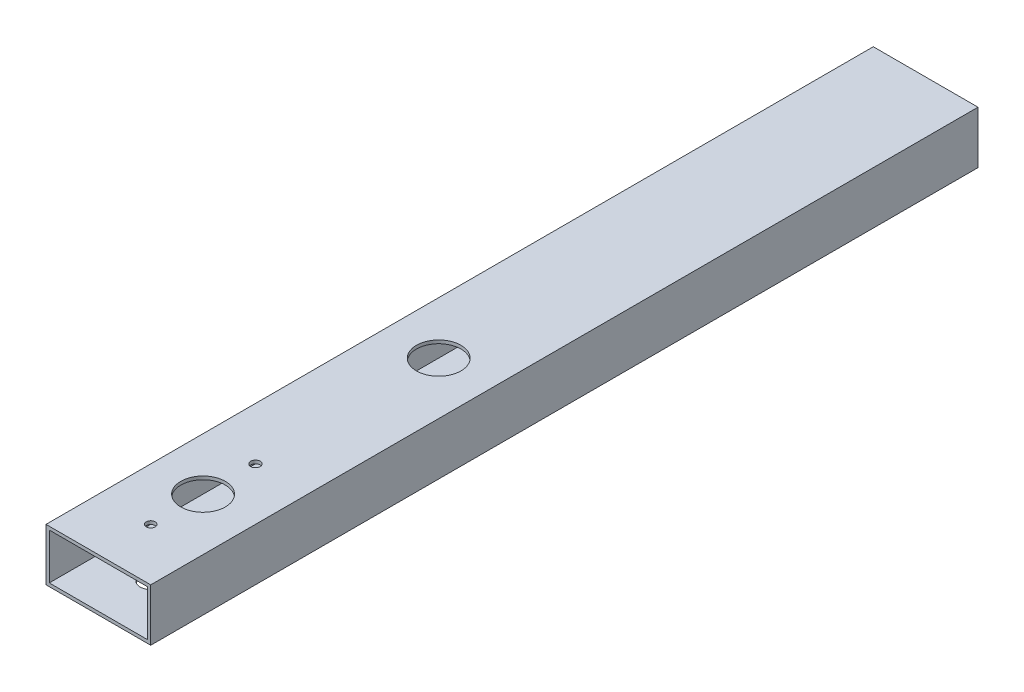
SolidWorks part; units mm, degrees
ref_plane "Front Plane" through (0, 0, 0) normal (0, 0, 1) x (1, 0, 0)
ref_plane "Top Plane" through (0, 0, 0) normal (0, 1, 0) x (1, 0, 0)
ref_plane "Right Plane" through (0, 0, 0) normal (1, 0, 0) x (0, 0, -1)
sketch "Sketch1" plane through (0, 0, 0) normal (0, 0, 1) x (1, 0, 0)
  line L0 (1.5875, 1.5875) -> (1.5875, 23.8125)
  line L1 (0, 0) -> (50.8, 0)
  line L2 (0, 0) -> (0, 25.4)
  line L3 (0, 25.4) -> (50.8, 25.4)
  line L4 (50.8, 0) -> (50.8, 25.4)
  line L5 (1.5875, 23.8125) -> (49.2125, 23.8125)
  line L6 (49.2125, 1.5875) -> (49.2125, 23.8125)
  line L7 (1.5875, 1.5875) -> (49.2125, 1.5875)
  dimension "D1" = 25.4
  dimension "D2" = 50.8
  dimension "D3" = 1.5875
extrude "Boss-Extrude1" add sketch "Sketch1" along normal blind 401.32
sketch "Sketch2" plane through (0, 25.4, 0) normal (0, 1, 0) x (1, 0, 0)
  line L1 (50.8, -401.32) -> (0, -401.32) construction
  line L2 (50.8, -401.32) -> (50.8, 0) construction
  circle A1 centre (25.4, -236.22) radius 10.795
  dimension "D1" = 21.59
  dimension "D2" = 165.1
  dimension "D6" = 25.4
extrude "Cut-Extrude1" cut sketch "Sketch2" against normal blind 2.54
sketch "Sketch3" plane through (0, 25.4, 0) normal (0, 1, 0) x (1, 0, 0)
  line L0 (50.8, -401.32) -> (50.8, 0) construction
  line L1 (50.8, -401.32) -> (0, -401.32) construction
  circle A0 centre (25.4, -350.52) radius 10.795
  dimension "D1" = 21.59
  dimension "D2" = 25.4
  dimension "D3" = 50.8
extrude "Cut-Extrude2" cut sketch "Sketch3" against normal blind 4.92
sketch "Sketch5" plane through (0, 1.5875, 0) normal (0, 1, 0) x (1, 0, 0)
  line L0 (50.8, -401.32) -> (50.8, 0) construction
  line L1 (1.5875, -401.32) -> (49.2125, -401.32) construction
  circle A0 centre (25.4, -236.22) radius 14.351
  dimension "D1" = 28.702
  dimension "D2" = 25.4
  dimension "D3" = 165.1
extrude "Cut-Extrude3" cut sketch "Sketch5" against normal blind 12.7
sketch "Sketch6" plane through (0, 1.5875, 0) normal (0, 1, 0) x (1, 0, 0)
  circle A0 centre (25.4, -350.52) radius 14.351
  dimension "D1" = 28.702
extrude "Cut-Extrude4" cut sketch "Sketch6" against normal blind 12.7
sketch "Sketch7" plane through (0, 25.4, 0) normal (0, 1, 0) x (1, 0, 0)
  line L0 (50.8, -401.32) -> (0, -401.32) construction
  line L1 (50.8, -401.32) -> (50.8, 0) construction
  circle A0 centre (25.4, -375.92) radius 2.159
  point P4 (0, 0)
  dimension "D1" = 4.318
  dimension "D2" = 25.4
  dimension "D3" = 25.4
extrude "Cut-Extrude5" cut sketch "Sketch7" against normal blind 2.54
sketch "Sketch9" plane through (0, 1.5875, 0) normal (0, 1, 0) x (1, 0, 0)
  line L0 (50.8, -401.32) -> (0, -401.32) construction
  line L1 (0, -401.32) -> (0, 0) construction
  circle A0 centre (25.4, -375.92) radius 5.08
  dimension "D1" = 25.4
  dimension "D2" = 25.4
  dimension "D3" = 10.16
extrude "Cut-Extrude6" cut sketch "Sketch9" against normal blind 2.54
sketch "Sketch10" plane through (0, 25.4, 0) normal (0, 1, 0) x (1, 0, 0)
  line L0 (50.8, -401.32) -> (50.8, 0) construction
  circle A0 centre (25.4, -325.12) radius 2.286
  circle A1 centre (25.4, -350.52) radius 10.795 construction
  dimension "D1" = 4.572
  dimension "D2" = 25.4
  dimension "D3" = 25.4
extrude "Cut-Extrude7" cut sketch "Sketch10" against normal blind 2.54
sketch "Sketch11" plane through (0, 1.5875, 0) normal (0, 1, 0) x (1, 0, 0)
  circle A0 centre (25.4, -325.12) radius 5.08
  dimension "D1" = 10.16
extrude "Cut-Extrude8" cut sketch "Sketch11" against normal blind 2.54
